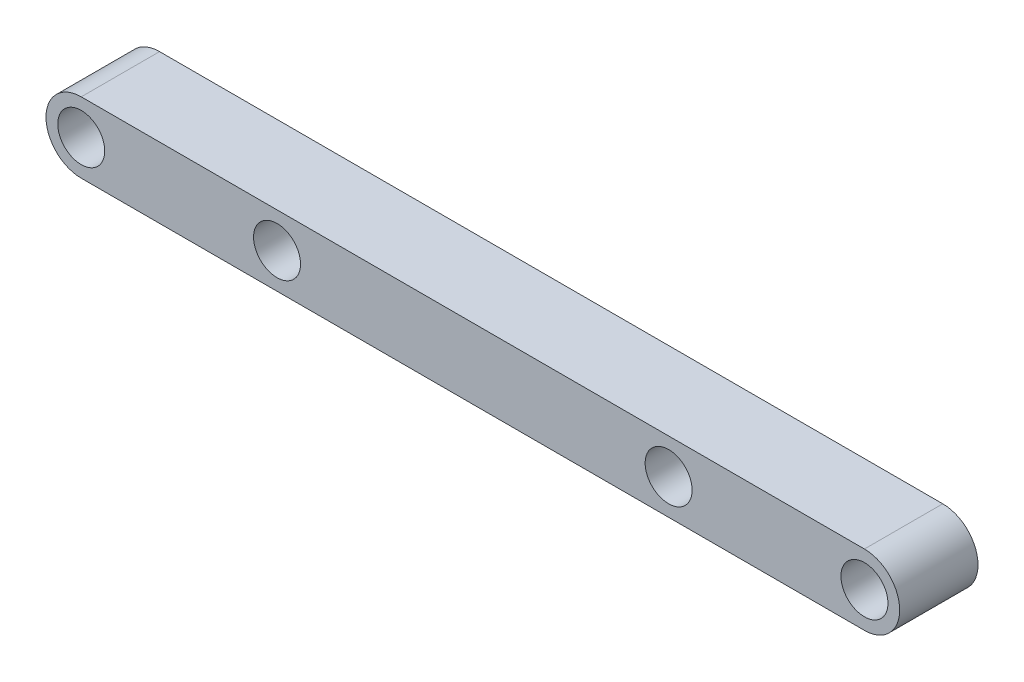
SolidWorks part; units mm, degrees
ref_plane "Front Plane" through (0, 0, 0) normal (0, 0, 1) x (1, 0, 0)
ref_plane "Top Plane" through (0, 0, 0) normal (0, 1, 0) x (1, 0, 0)
ref_plane "Right Plane" through (0, 0, 0) normal (1, 0, 0) x (0, 0, -1)
sketch "Sketch1" plane through (0, 0, 0) normal (0, 0, 1) x (1, 0, 0)
  line L0 (-10.7411, 1.3365) -> (98.2589, 1.3365) construction
  line L1 (-6.2411, 5.8365) -> (93.7589, 5.8365)
  line L3 (-6.2411, -3.1635) -> (93.7589, -3.1635)
  circle A0 centre (-6.2411, 1.3365) radius 3
  arc A1 (-6.2411, 5.8365) -> (-6.2411, -3.1635) centre (-6.2411, 1.3365) ccw
  circle A2 centre (68.7589, 1.3365) radius 3
  circle A3 centre (93.7589, 1.3365) radius 3
  arc A4 (93.7589, -3.1635) -> (93.7589, 5.8365) centre (93.7589, 1.3365) ccw
  circle A5 centre (18.7589, 1.3365) radius 3
  dimension "D2" = 6
  dimension "D3" = 6
  dimension "D4" = 6
  dimension "D5" = 25
  dimension "D6" = 6
  dimension "D7" = 25
  dimension "D8" = 50
  dimension "D1" = 4.5
extrude "Boss-Extrude1" add sketch "Sketch1" along normal blind 10
